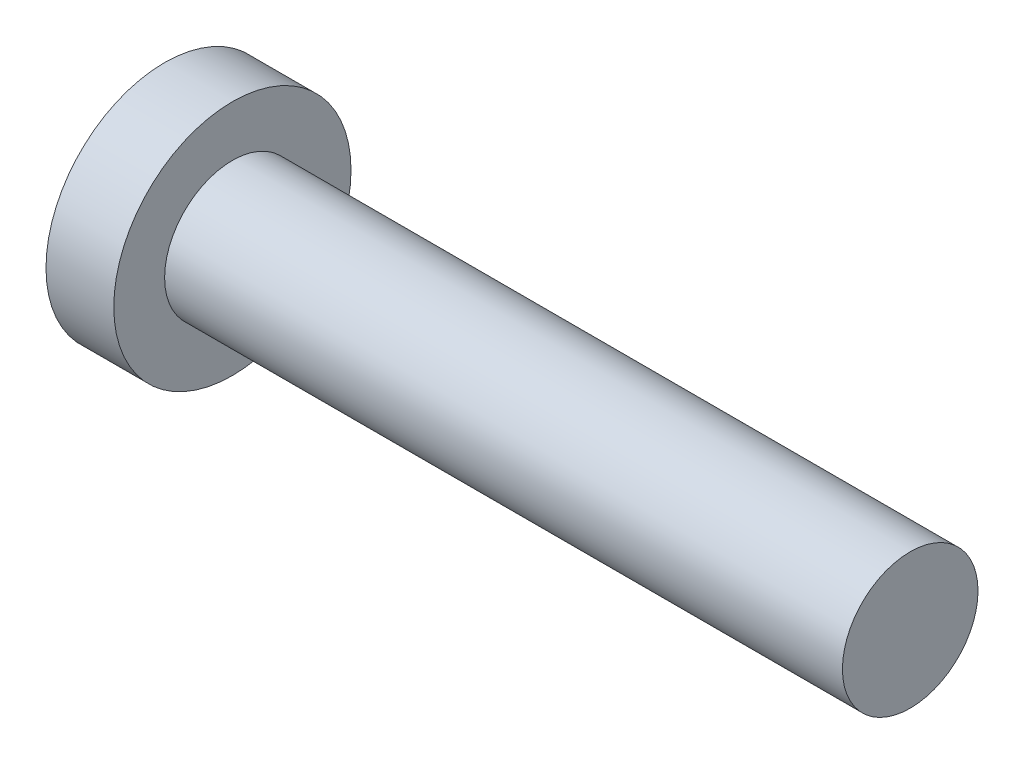
SolidWorks part; units mm, degrees
ref_plane "前视基准面" through (0, 0, 0) normal (0, 0, 1) x (1, 0, 0)
ref_plane "上视基准面" through (0, 0, 0) normal (0, 1, 0) x (1, 0, 0)
ref_plane "右视基准面" through (0, 0, 0) normal (1, 0, 0) x (0, 0, -1)
sketch "草图1" plane through (0, 0, 0) normal (1, 0, 0) x (0, 0, -1)
  circle A0 centre (0, 0) radius 1
  dimension "D1" = 2
extrude "凸台-拉伸1" add sketch "草图1" along normal blind 10
sketch "草图2" plane through (0, 0, 0) normal (-1, 0, 0) x (0, 0, 1)
  circle A0 centre (0, 0) radius 1.75
  dimension "D1" = 3.5
extrude "凸台-拉伸2" add sketch "草图2" along normal blind 1
